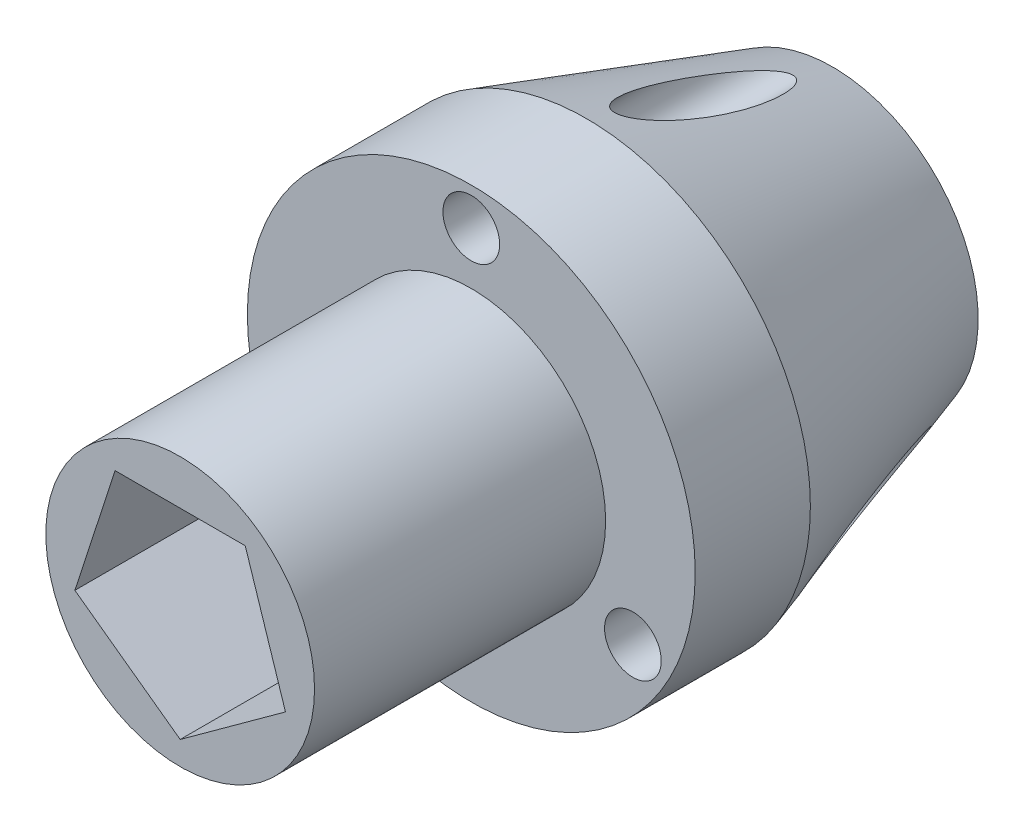
SolidWorks part; units mm, degrees
ref_plane "Front Plane" through (0, 0, 0) normal (0, 0, 1) x (1, 0, 0)
ref_plane "Top Plane" through (0, 0, 0) normal (0, 1, 0) x (1, 0, 0)
ref_plane "Right Plane" through (0, 0, 0) normal (1, 0, 0) x (0, 0, -1)
ref_plane "Plane1" through (0, 0, 0) normal (0, -1, 0) x (1, 0, 0)
sketch "Sketch1" plane through (0, 0, 0) normal (0, -1, 0) x (1, 0, 0)
  line L0 (15, 24.2) -> (0, 24.2)
  line L1 (0, 24.2) -> (0, 0)
  line L2 (0, 0) -> (9.7545, 0)
  line L3 (9.7545, 0) -> (15, 16.4857)
  line L4 (15, 16.4857) -> (15, 24.2)
  line L5 (0, 24.2) -> (0, 0) construction
revolve "Revolve1" add sketch "Sketch1" angle 360 about L5
sketch "Sketch2" plane through (0, 0, 24.2) normal (0, 0, 1) x (1, 0, 0)
  circle A0 centre (0, 0) radius 9
extrude "Boss-Extrude1" add sketch "Sketch2" along normal blind 19.5
sketch "Sketch3" plane through (0, 0, 0) normal (0, 0, -1) x (-1, 0, 0)
  line L0 (0, -7.4164) -> (7.0534, -2.2918)
  line L1 (7.0534, -2.2918) -> (4.3593, 6)
  line L2 (4.3593, 6) -> (-4.3593, 6)
  line L3 (-4.3593, 6) -> (-7.0534, -2.2918)
  line L4 (-7.0534, -2.2918) -> (0, -7.4164)
extrude "Cut-Extrude1" cut sketch "Sketch3" against normal through all
hole_wizard "Ø3.8 (3.8) Diameter Hole1" positions "Sketch5" profile "Sketch4" hole size "Ø3.8" standard "ANSI Metric"
sketch "Sketch5" plane through (0, 0, 24.2) normal (0, 0, 1) x (1, 0, 0)
  point P0 (10.8253, -6.25)
  point P1 (-10.8253, -6.25)
  point P2 (0, 12.5)
sketch "Sketch4" plane through (10.8253, -6.25, 24.2) normal (1, 0, 0) x (0, -1, 0)
  line L0 (0, 0) -> (0, 24.2)
  line L1 (0, 24.2) -> (1.9, 24.2)
  line L2 (1.9, 24.2) -> (1.9, 0)
  line L5 (1.9, 0) -> (0, 0)
  line L11 (0, -6.35) -> (0, 107.95) construction
  dimension "Thru Hole Dia." = 3.8
  dimension "Thru Hole Depth" = 24.2
